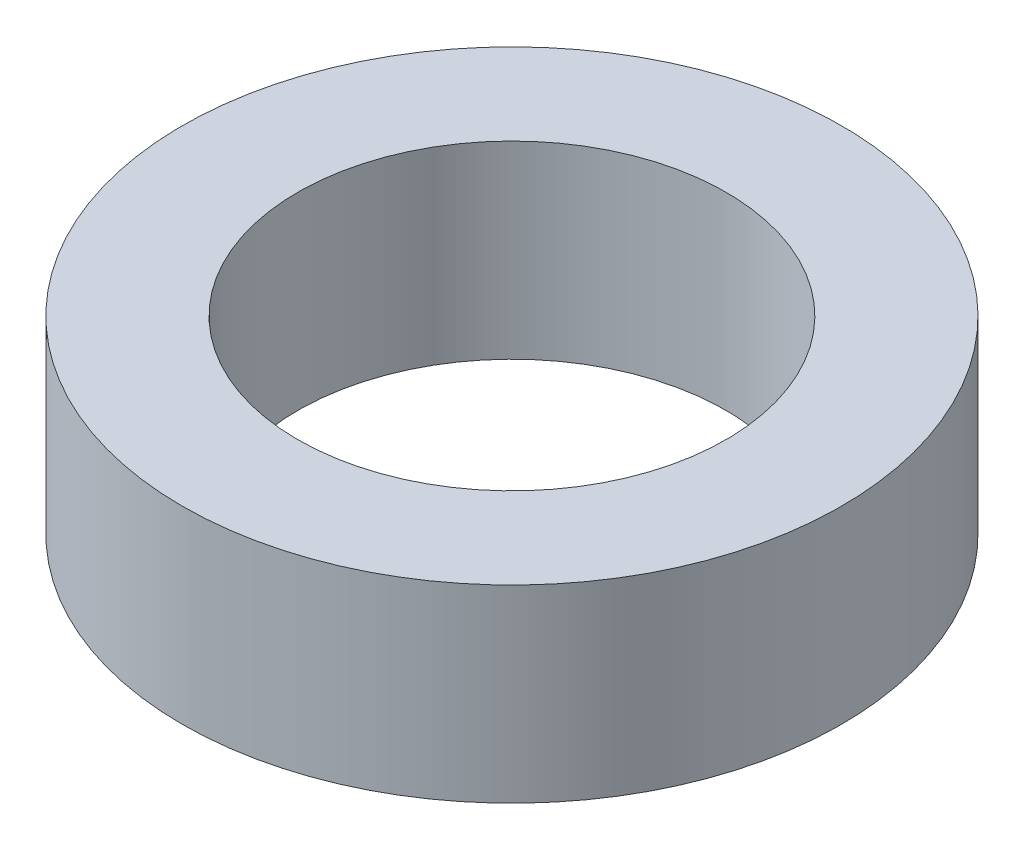
SolidWorks part; units mm, degrees
ref_plane "Front Plane" through (0, 0, 0) normal (0, 0, 1) x (1, 0, 0)
ref_plane "Top Plane" through (0, 0, 0) normal (0, 1, 0) x (1, 0, 0)
ref_plane "Right Plane" through (0, 0, 0) normal (1, 0, 0) x (0, 0, -1)
sketch "Sketch1" plane through (0, 0, 0) normal (0, 1, 0) x (1, 0, 0)
  circle A0 centre (0, 0) radius 3
extrude "Boss-Extrude1" add sketch "Sketch1" along normal blind 1.72
hole_wizard "M3.5 Clearance Hole1" positions "Sketch3" profile "Sketch4" hole size "M3.5" standard "ANSI Metric" end condition through all
sketch "Sketch3" plane through (0, 1.72, 0) normal (0, 1, 0) x (1, 0, 0)
  point P0 (0, 0)
sketch "Sketch4" plane through (0, 1.72, 0) normal (1, 0, 0) x (0, 0, 1)
  line L0 (0, 0) -> (0, 1.72)
  line L1 (0, 1.72) -> (1.95, 1.72)
  line L2 (1.95, 1.72) -> (1.95, 0)
  line L5 (1.95, 0) -> (0, 0)
  line L11 (0, -6.35) -> (0, 107.95) construction
  dimension "Thru Hole Dia." = 3.9
  dimension "Thru Hole Depth" = 1.72
